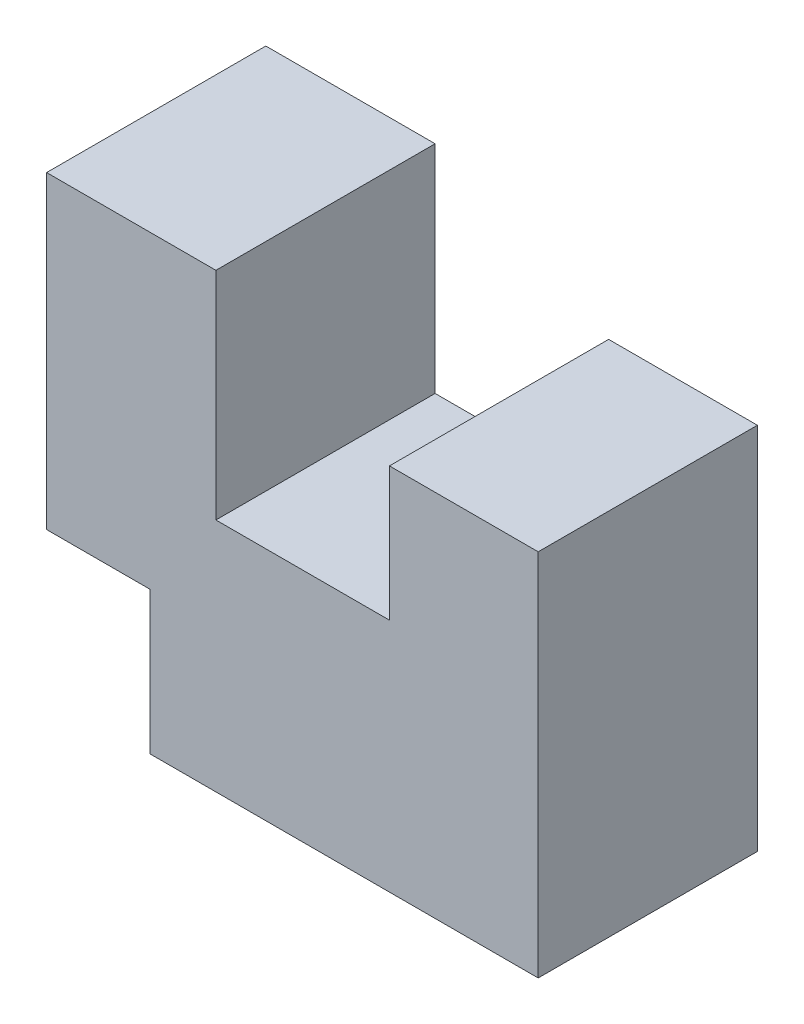
SolidWorks part; units mm, degrees
ref_plane "Plan de face" through (0, 0, 0) normal (0, 0, 1) x (1, 0, 0)
ref_plane "Plan de dessus" through (0, 0, 0) normal (0, 1, 0) x (1, 0, 0)
ref_plane "Plan de droite" through (0, 0, 0) normal (1, 0, 0) x (0, 0, -1)
sketch "Esquisse1" plane through (0, 0, 0) normal (0, 0, 1) x (1, 0, 0)
  line L0 (0, 0) -> (0, 56.4256)
  line L1 (0, 56.4256) -> (30.8949, 56.4256)
  line L2 (30.8949, 56.4256) -> (30.8949, 16.9654)
  line L3 (30.8949, 16.9654) -> (62.5636, 16.9654)
  line L4 (62.5636, 16.9654) -> (62.5636, 41.3452)
  line L5 (62.5636, 41.3452) -> (89.7082, 41.3452)
  line L6 (89.7082, 41.3452) -> (89.7082, -26.0136)
  line L7 (89.7082, -26.0136) -> (18.8307, -26.0136)
  line L8 (18.8307, -26.0136) -> (18.8307, 0)
  line L9 (18.8307, 0) -> (0, 0)
extrude "Boss.-Extru.1" add sketch "Esquisse1" along normal blind 40
